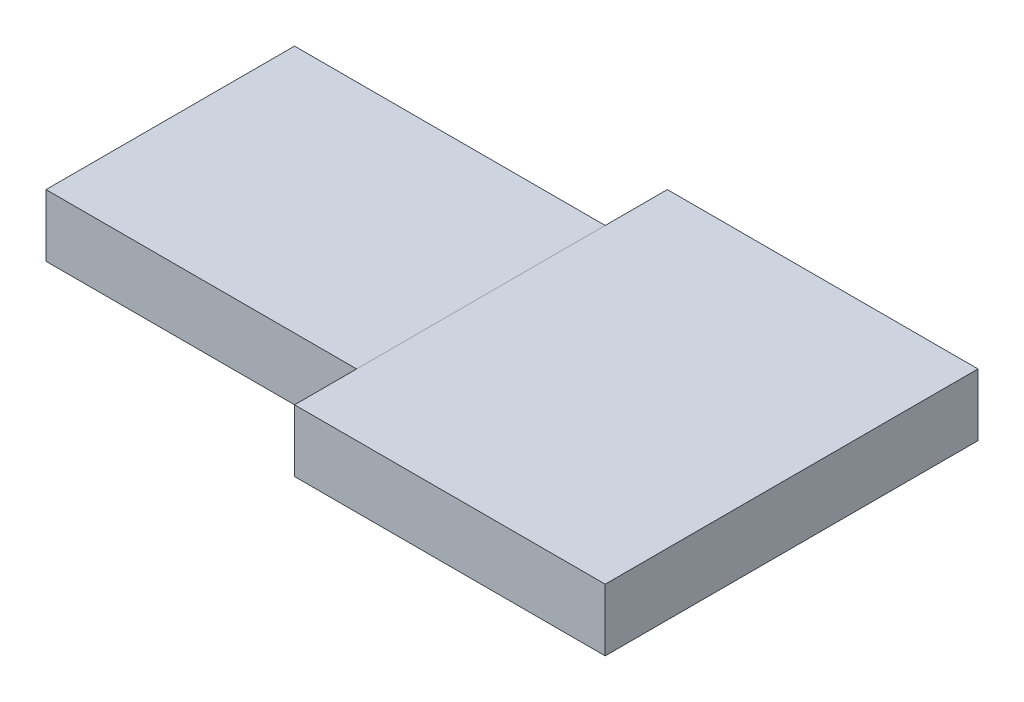
SolidWorks part; units mm, degrees
other "Connection Feature"
ref_plane "Front Plane" through (0, 0, 0) normal (0, 0, 1) x (1, 0, 0)
ref_plane "Top Plane" through (0, 0, 0) normal (0, 1, 0) x (1, 0, 0)
ref_plane "Right Plane" through (0, 0, 0) normal (1, 0, 0) x (0, 0, -1)
sketch "Sketch1" plane through (0, 0, 0) normal (0, 1, 0) x (1, 0, 0)
  line L1 (-50, -30) -> (50, -30)
  line L2 (-50, -30) -> (-50, 30)
  line L3 (-50, 30) -> (50, 30)
  line L4 (50, -30) -> (50, 30)
  line L5 (-50, -30) -> (50, 30) construction
  line L6 (-50, 30) -> (50, -30) construction
  point P0 (0, 0)
  dimension "D1" = 60
  dimension "D2" = 100
extrude "Boss-Extrude1" add sketch "Sketch1" along normal mid plane 10
sketch "Sketch2" plane through (0, 5, 0) normal (0, 1, 0) x (1, 0, 0)
  line L1 (-50, 30) -> (0, 30)
  line L2 (-50, 30) -> (-50, 20)
  line L3 (-50, 20) -> (0, 20)
  line L4 (0, 30) -> (0, 20)
  line L5 (-50, -30) -> (0, -30)
  line L6 (-50, -30) -> (-50, -20)
  line L7 (-50, -20) -> (0, -20)
  line L8 (0, -30) -> (0, -20)
  dimension "D1" = 10
extrude "Cut-Extrude1" cut sketch "Sketch2" against normal through all
sketch "Sketch3" plane through (0, 5, 0) normal (0, 1, 0) x (1, 0, 0)
  line L0 (-50, 20) -> (0, 20) construction
  line L1 (-50, 20) -> (-50, -20) construction
  line L2 (0, -20) -> (-50, -20) construction
  line L3 (-50, 20) -> (0, 20)
  line L4 (-50, 20) -> (-50, -20)
  line L5 (0, -20) -> (-50, -20)
  line L6 (0, 20) -> (0, -20)
extrude "Cut-Extrude2" cut sketch "Sketch3" against normal blind 0.001
mirror "Mirror1" about plane through (0, 0, 0) normal (0, 1, 0) of "Cut-Extrude2"
